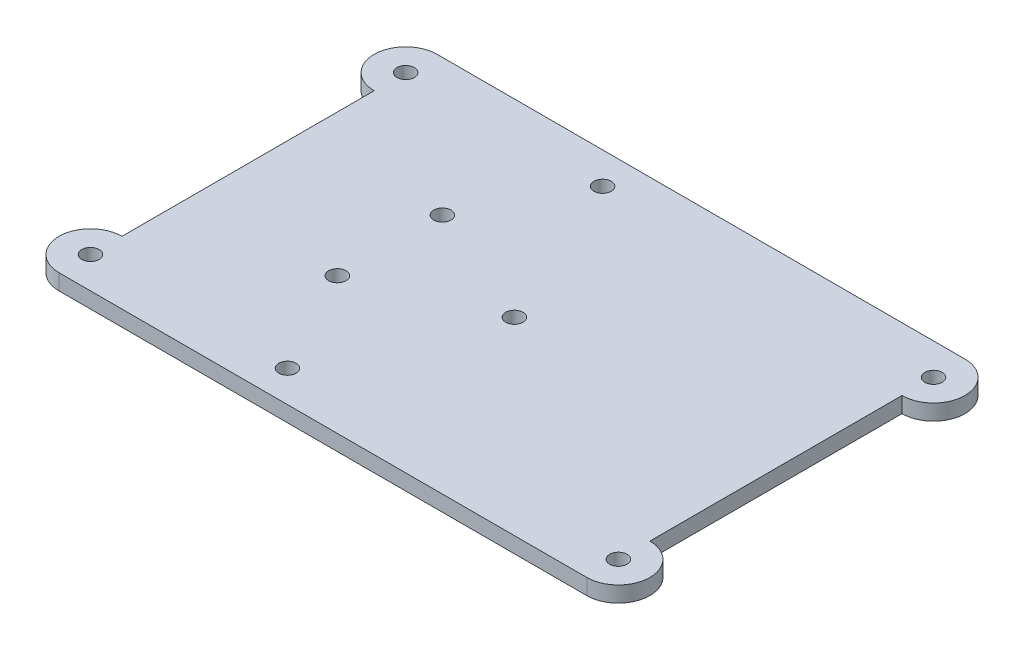
SolidWorks part; units mm, degrees
ref_plane "前视" through (0, 0, 0) normal (0, 0, 1) x (1, 0, 0)
ref_plane "上视" through (0, 0, 0) normal (0, 1, 0) x (1, 0, 0)
ref_plane "右视" through (0, 0, 0) normal (1, 0, 0) x (0, 0, -1)
sketch "草图1" plane through (0, 0, 0) normal (0, 1, 0) x (1, 0, 0)
  line L0 (71.8743, 41.9274) -> (71.8743, -6.0726)
  line L2 (-28.6257, 41.9274) -> (-28.6257, -6.0726)
  line L4 (-28.6257, 53.9274) -> (71.8743, 53.9274)
  line L9 (-28.6257, -18.0726) -> (71.8743, -18.0726)
  circle A0 centre (-28.6257, 47.9274) radius 1.65
  circle A1 centre (8.8743, 47.9274) radius 1.65
  circle A2 centre (71.8743, 47.9274) radius 1.65
  circle A3 centre (-28.6257, -12.0726) radius 1.65
  circle A4 centre (8.8743, -12.0726) radius 1.65
  circle A5 centre (71.8743, -12.0726) radius 1.65
  arc A6 (-28.6257, 53.9274) -> (-28.6257, 41.9274) centre (-28.6257, 47.9274) ccw
  arc A8 (71.8743, 41.9274) -> (71.8743, 53.9274) centre (71.8743, 47.9274) ccw
  arc A9 (71.8743, -18.0726) -> (71.8743, -6.0726) centre (71.8743, -12.0726) ccw
  arc A11 (-28.6257, -6.0726) -> (-28.6257, -18.0726) centre (-28.6257, -12.0726) ccw
  circle A12 centre (-1.6257, 27.9274) radius 1.65
  circle A13 centre (-1.6257, 7.9274) radius 1.65
  circle A18 centre (22.0743, 17.9274) radius 1.65
extrude "凸台-拉伸1" add sketch "草图1" along normal blind 3
